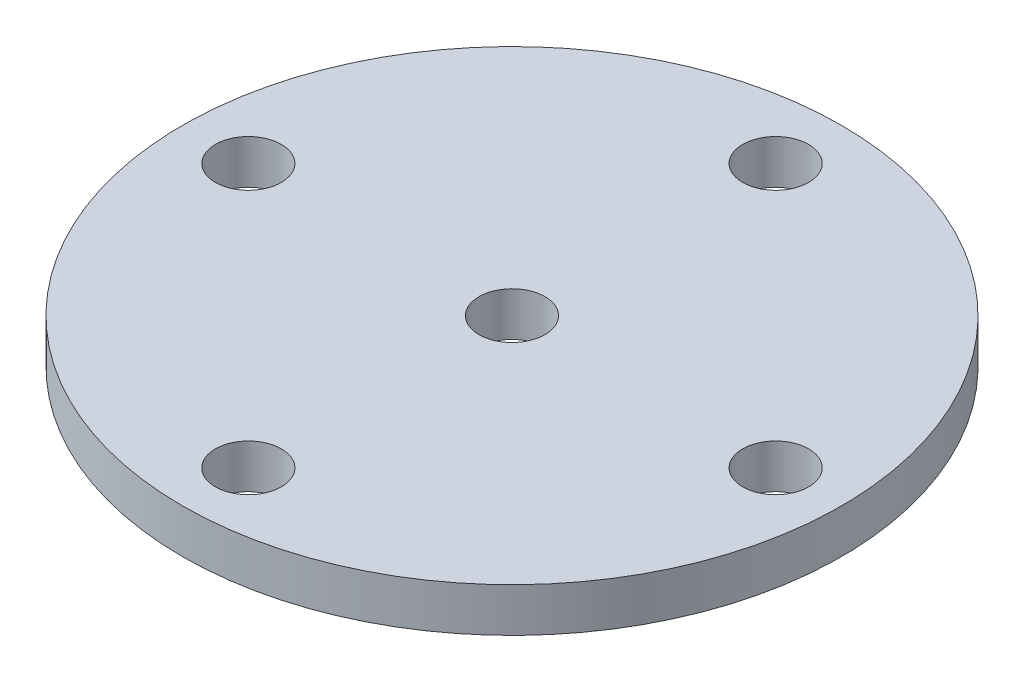
SolidWorks part; units mm, degrees
ref_plane "Alzado" through (0, 0, 0) normal (0, 0, 1) x (1, 0, 0)
ref_plane "Planta" through (0, 0, 0) normal (0, 1, 0) x (1, 0, 0)
ref_plane "Vista lateral" through (0, 0, 0) normal (1, 0, 0) x (0, 0, -1)
sketch "Croquis1" plane through (0, 0, 0) normal (0, 1, 0) x (1, 0, 0)
  line L0 (0, 0) -> (0, 51.3329) construction
  line L1 (0, 0) -> (57.0814, 0) construction
  circle A0 centre (0, 0) radius 1.5
  circle A1 centre (0, 0) radius 15
  circle A2 centre (-12, 0) radius 1.5
  circle A3 centre (12, 0) radius 1.5
  circle A4 centre (0, 12) radius 1.5
  circle A5 centre (0, -12) radius 1.5
  dimension "D1" = 30
  dimension "D2" = 3
  dimension "D3" = 12
  dimension "D4" = 12
extrude "Saliente-Extruir1" add sketch "Croquis1" along normal blind 2
